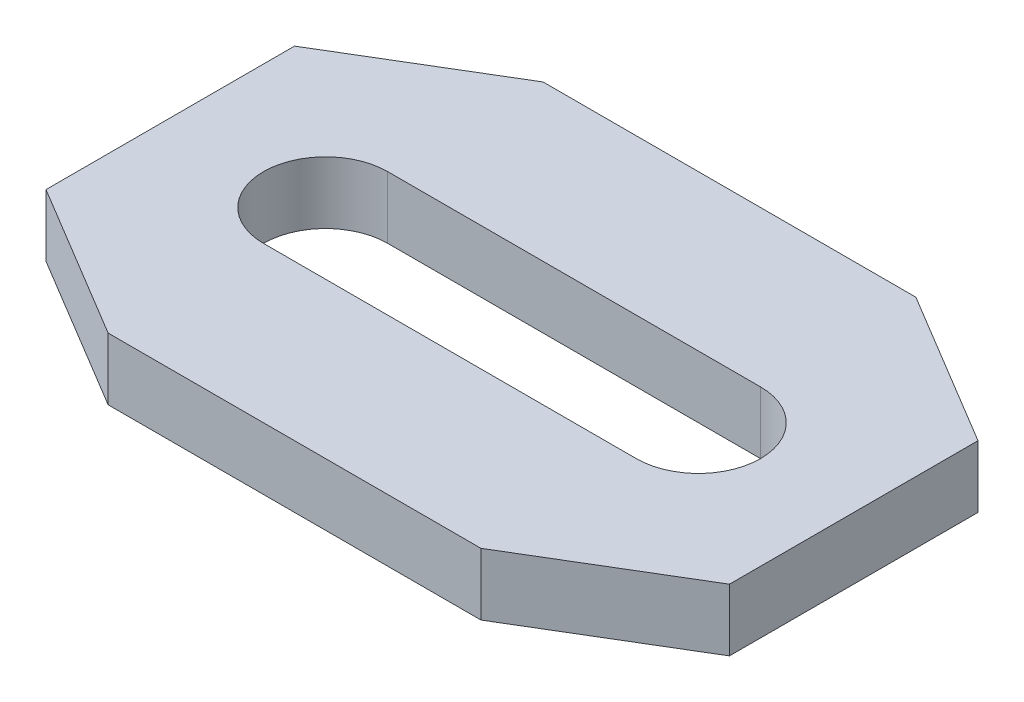
SolidWorks part; units mm, degrees
ref_plane "Front Plane" through (0, 0, 0) normal (0, 0, 1) x (1, 0, 0)
ref_plane "Top Plane" through (0, 0, 0) normal (0, 1, 0) x (1, 0, 0)
ref_plane "Right Plane" through (0, 0, 0) normal (1, 0, 0) x (0, 0, -1)
sketch "Sketch2" plane through (0, 0, 0) normal (0, 1, 0) x (1, 0, 0)
  line L0 (0, 44.45) -> (-31.75, 25.4)
  line L1 (-31.75, 25.4) -> (-31.75, -25.4)
  line L2 (-31.75, -25.4) -> (0, -44.45)
  line L3 (0, -44.45) -> (76.2, -44.45)
  line L4 (76.2, -44.45) -> (107.95, -25.4)
  line L5 (107.95, -25.4) -> (107.95, 25.4)
  line L6 (107.95, 25.4) -> (76.2, 44.45)
  line L7 (76.2, 44.45) -> (0, 44.45)
  line L8 (0, 0) -> (76.2, 0) construction
  line L9 (0, 12.7) -> (76.2, 12.7)
  line L10 (0, -12.7) -> (76.2, -12.7)
  arc A0 (0, 12.7) -> (0, -12.7) centre (0, 0) ccw
  arc A1 (76.2, -12.7) -> (76.2, 12.7) centre (76.2, 0) ccw
  point P11 (38.1, 0)
  dimension "D1" = 31.75
  dimension "D2" = 31.75
  dimension "D3" = 31.75
  dimension "D4" = 31.75
  dimension "D5" = 76.2
  dimension "D6" = 50.8
  dimension "D7" = 19.05
  dimension "D8" = 19.05
  dimension "D9" = 19.05
  dimension "D10" = 25.4
  dimension "D11" = 25.4
extrude "Boss-Extrude1" add sketch "Sketch2" along normal blind 12.7
